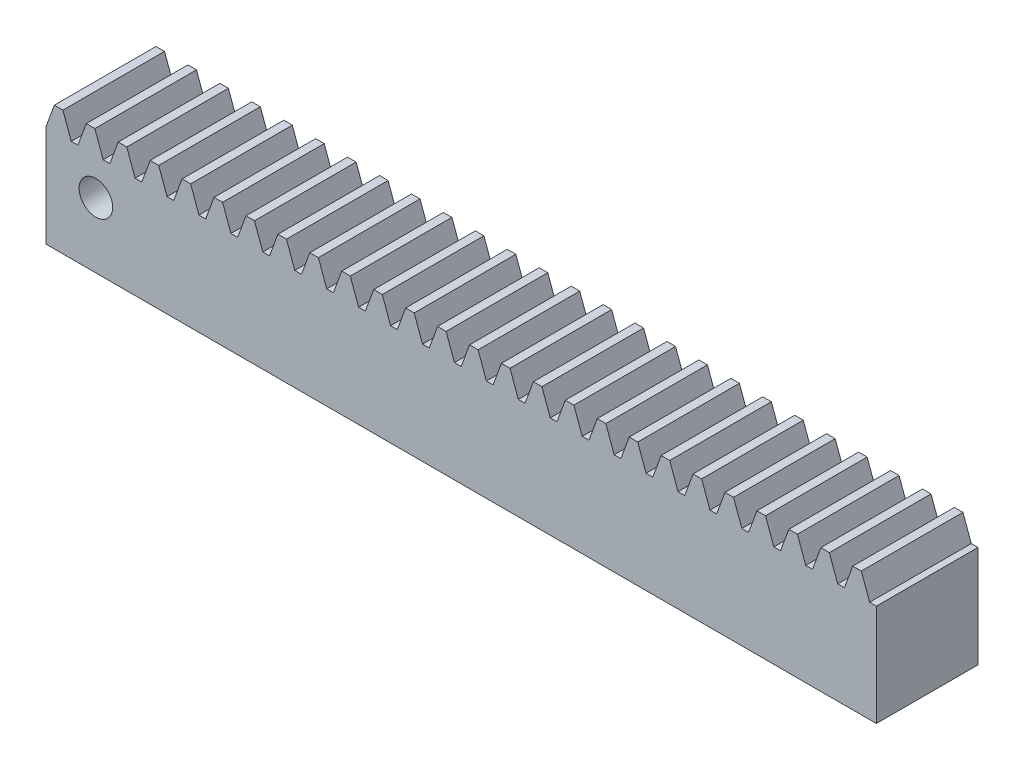
SolidWorks part; units mm, degrees
ref_plane "前视基准面" through (0, 0, 0) normal (0, 0, 1) x (1, 0, 0)
ref_plane "上视基准面" through (0, 0, 0) normal (0, 1, 0) x (1, 0, 0)
ref_plane "右视基准面" through (0, 0, 0) normal (1, 0, 0) x (0, 0, -1)
sketch "草图1" plane through (0, 0, 0) normal (0, 0, 1) x (1, 0, 0)
  line L1 (0, 0) -> (81.6814, 0)
  line L2 (0, 0) -> (0, -10)
  line L3 (0, -10) -> (81.6814, -10)
  line L4 (81.6814, 0) -> (81.6814, -10)
  dimension "D1" = 10
  dimension "L" = 81.6814
extrude "拉伸1" add sketch "草图1" along normal blind 30
sketch "草图2" plane through (0, 0, 30) normal (0, 0, 1) x (1, 0, 0)
  line L0 (0, 0) -> (0.8189, 2.25)
  line L1 (0.8189, 2.25) -> (1.6618, 2.25)
  line L2 (1.6618, 2.25) -> (2.4807, 0)
  line L3 (81.6814, 0) -> (0, 0) construction
  line L4 (0, 0) -> (2.4807, 0)
  line L5 (0.455, 1.25) -> (2.0258, 1.25) construction
  dimension "D2" = 70
  dimension "alpha" = 110
  dimension "ha" = 1
  dimension "hf" = 1.25
  dimension "S" = 1.5708
extrude "拉伸2" add sketch "草图2" against normal up to surface (30 mm away) up to face at (40.8407, -5, 0)
pattern_linear "阵列(线性)1" count 26 spacing 3.1416 along (1, 0, 0) of "拉伸2"
sketch "草图3" plane through (0, 0, 0) normal (0, 0, -1) x (-1, 0, 0)
  line L1 (-84.9157, 7.3239) -> (2.3937, 7.3239)
  line L2 (-84.9157, 7.3239) -> (-84.9157, -14.5335)
  line L3 (-84.9157, -14.5335) -> (2.3937, -14.5335)
  line L4 (2.3937, 7.3239) -> (2.3937, -14.5335)
extrude "切除-拉伸1" cut sketch "草图3" against normal offset from surface (20 mm away) 10 up to face at (40.9853, 0.896, 30)
sketch "Sketch1" plane through (0, -10, 0) normal (0, -1, 0) x (1, 0, 0)
  line L0 (-0.9454, 27.5) -> (129.7526, 27.5) construction
sketch "草图4" plane through (0, 0, 20) normal (0, 0, -1) x (-1, 0, 0)
  line L0 (0, -10) -> (-81.6814, -10) construction
  circle A0 centre (-4.9065, -3.6) radius 1.65
  dimension "D1" = 3.3
  dimension "D2" = 6.4
extrude "切除-拉伸4" cut sketch "草图4" against normal through all
ref_plane "Plane1" through (0, 0, 25) normal (0, 0, 1) x (1, 0, 0)
equation "\"D2@草图2\" = 180 - \"alpha@草图2\""
equation "\"Z@阵列(线性)1\" = \"L@草图1\" /  ( \"S@草图2\" * 2 ) "
equation "\"D3@阵列(线性)1\" = \"S@草图2\" * 2"
equation "\"mm\"=4"
